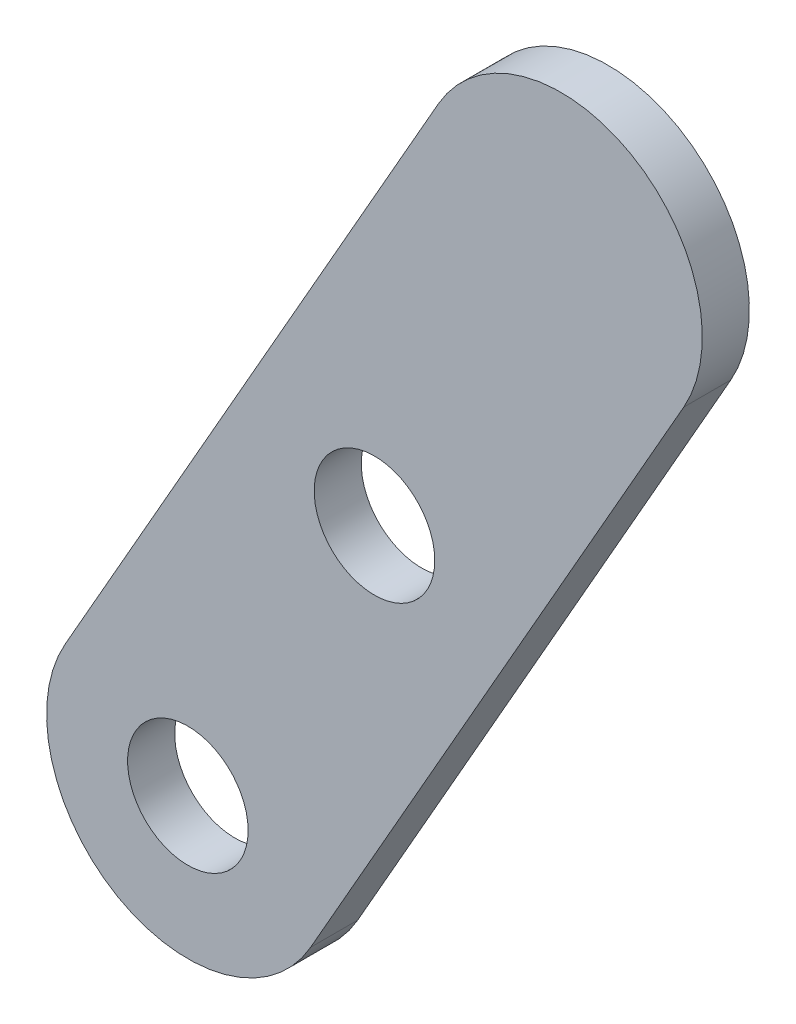
SolidWorks part; units mm, degrees
ref_plane "Front Plane" through (0, 0, 0) normal (0, 0, 1) x (1, 0, 0)
ref_plane "Top Plane" through (0, 0, 0) normal (0, 1, 0) x (1, 0, 0)
ref_plane "Right Plane" through (0, 0, 0) normal (1, 0, 0) x (0, 0, -1)
sketch "Sketch1" plane through (0, 0, 0) normal (0, 0, 1) x (1, 0, 0)
  line L6 (0, 0) -> (12.5817, 22.0649) construction
  line L7 (-4.1372, 2.3591) -> (8.4446, 24.424)
  line L8 (4.1372, -2.3591) -> (16.7189, 19.7058)
  circle A2 centre (0, 0) radius 2.032
  arc A6 (-4.1372, 2.3591) -> (4.1372, -2.3591) centre (0, 0) ccw
  arc A7 (16.7189, 19.7058) -> (8.4446, 24.424) centre (12.5817, 22.0649) ccw
  circle A8 centre (6.2909, 11.0325) radius 2.032
  point P3 (6.2909, 11.0325)
  dimension "D1" = 4.7625
  dimension "D2" = 4.064
extrude "Boss-Extrude1" add sketch "Sketch1" along normal blind 1.5875
